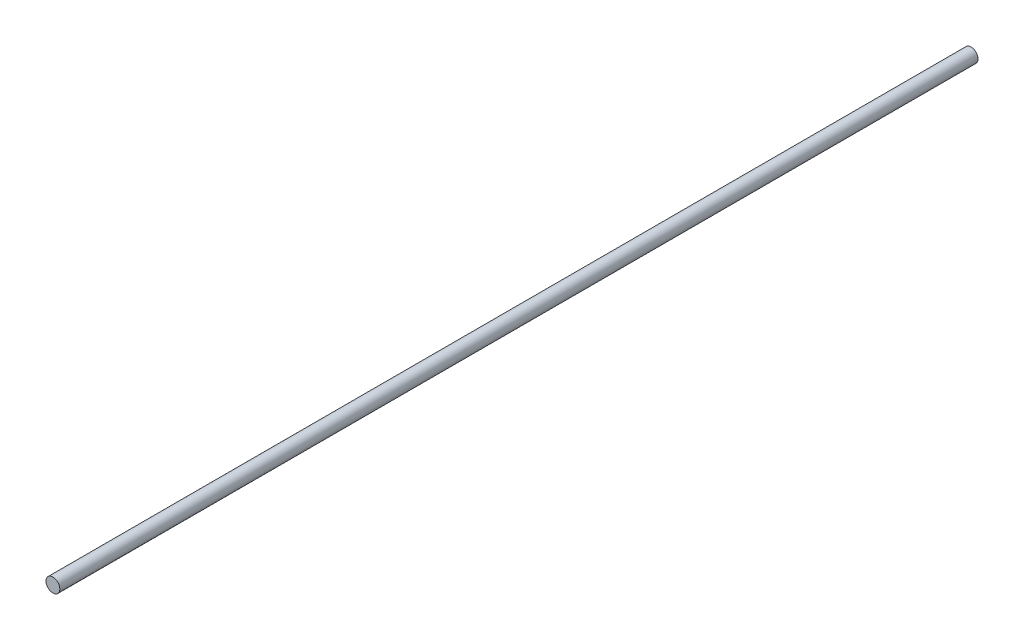
SolidWorks part; units mm, degrees
material "6061-T6 (SS)"
ref_plane "Front Plane" through (0, 0, 0) normal (0, 0, 1) x (1, 0, 0)
ref_plane "Top Plane" through (0, 0, 0) normal (0, 1, 0) x (1, 0, 0)
ref_plane "Right Plane" through (0, 0, 0) normal (1, 0, 0) x (0, 0, -1)
sketch "Sketch1" plane through (0, 0, 0) normal (0, 0, 1) x (1, 0, 0)
  circle A0 centre (0, 0) radius 4.7625
  dimension "D1" = 9.525
extrude "Boss-Extrude1" add sketch "Sketch1" along normal blind 631.2024
equation "\"load\" = 400"
equation "\"Max Deflection\" = 0.009"
equation "\"Elastic Modulus\"= 10000000"
equation "\"Diameter\"= 0.375"
equation "\"Area\"= PI * \"Diameter\" ^ 2 / 4"
equation "\"Length\"= \"Max Deflection\" * \"Area\" * \"Elastic Modulus\" / \"load\""
equation "\"D1@Sketch1\"=\"Diameter\""
equation "\"D1@Boss-Extrude1\"=\"Length\""
